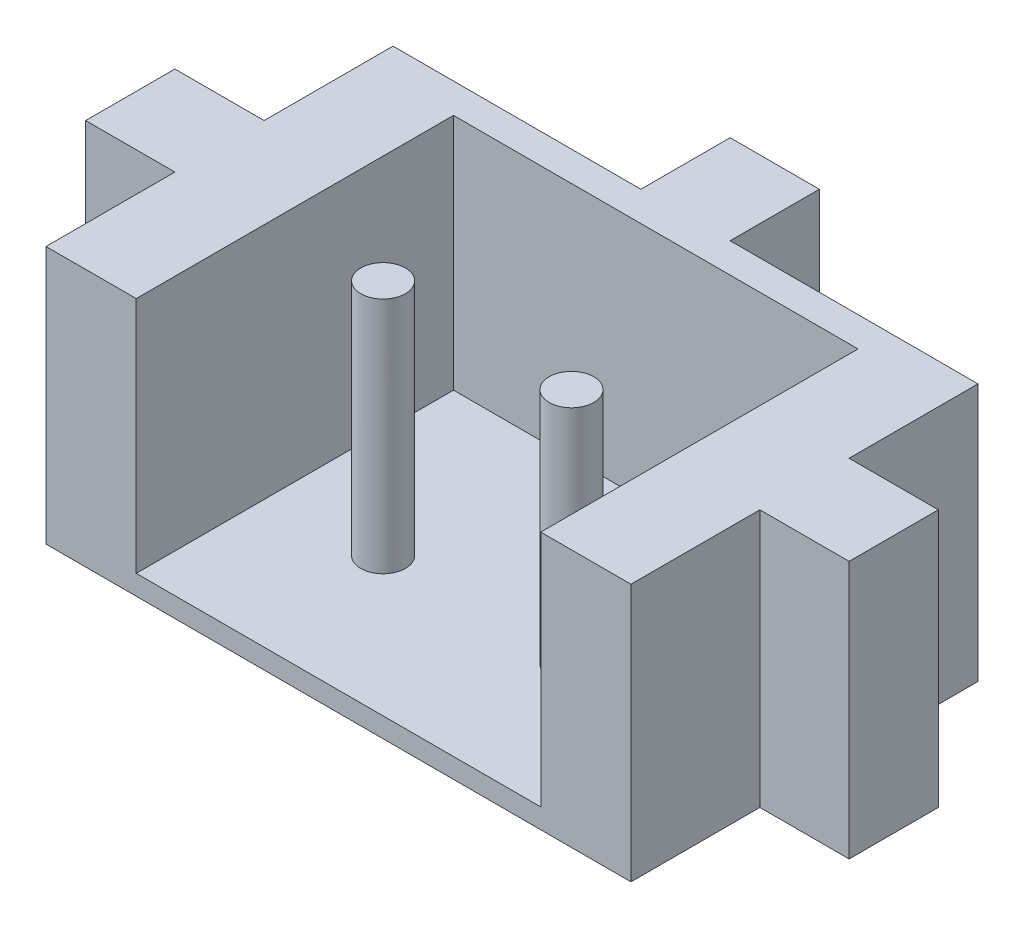
SolidWorks part; units mm, degrees
ref_plane "Alzado" through (0, 0, 0) normal (0, 0, 1) x (1, 0, 0)
ref_plane "Planta" through (0, 0, 0) normal (0, 1, 0) x (1, 0, 0)
ref_plane "Vista lateral" through (0, 0, 0) normal (1, 0, 0) x (0, 0, -1)
sketch "Croquis2" plane through (0, 0, 0) normal (0, 1, 0) x (1, 0, 0)
  line L0 (0, 10.287) -> (0, -10.6078) construction
  line L1 (14.75, -8.75) -> (-14.75, -8.75)
  line L2 (14.75, -8.75) -> (14.75, -2.25)
  line L3 (14.75, 8.75) -> (2.25, 8.75)
  line L4 (-14.75, -8.75) -> (-14.75, -2.25)
  line L5 (14.75, -8.75) -> (-14.75, 8.75) construction
  line L6 (14.75, 8.75) -> (-14.75, -8.75) construction
  line L7 (-10.7327, 0) -> (10.7937, 0) construction
  line L8 (19.25, -2.25) -> (14.75, -2.25)
  line L9 (2.25, 13.25) -> (-2.25, 13.25)
  line L10 (2.25, 13.25) -> (2.25, 8.75)
  line L12 (-2.25, 13.25) -> (-2.25, 8.75)
  line L13 (2.25, 13.25) -> (-2.25, 8.75) construction
  line L14 (2.25, 8.75) -> (-2.25, 13.25) construction
  line L15 (-19.25, 2.25) -> (-14.75, 2.25)
  line L16 (-19.25, 2.25) -> (-19.25, -2.25)
  line L17 (-19.25, -2.25) -> (-14.75, -2.25)
  line L19 (-19.25, 2.25) -> (-14.75, -2.25) construction
  line L20 (-19.25, -2.25) -> (-14.75, 2.25) construction
  line L22 (19.25, 2.25) -> (14.75, 2.25)
  line L23 (19.25, 2.25) -> (19.25, -2.25)
  line L32 (-2.25, 8.75) -> (-14.75, 8.75)
  line L33 (14.75, 2.25) -> (14.75, 8.75)
  line L34 (-14.75, 2.25) -> (-14.75, 8.75)
  point P0 (0, 0)
  point P10 (0, 11)
  point P15 (-17, 0)
  dimension "D1" = 4.5
  dimension "D2" = 4.5
  dimension "D3" = 4.5
  dimension "D4" = 4.5
  dimension "D5" = 29.5
  dimension "D6" = 17.5
extrude "Saliente-Extruir1" add sketch "Croquis2" along normal blind 13
sketch "Croquis4" plane through (0, 13, 0) normal (0, 1, 0) x (1, 0, 0)
  line L0 (-14.75, 8.75) -> (-14.75, -8.75) construction
  line L1 (-10.2, 7.25) -> (-10.2, -8.75)
  line L2 (-14.75, 8.75) -> (14.75, 8.75) construction
  line L3 (14.75, 8.75) -> (14.75, -8.75) construction
  line L6 (-10.2, 7.25) -> (10.2, 7.25)
  line L9 (0, 5.1469) -> (0, -6.906) construction
  line L10 (10.2, 7.25) -> (10.2, -8.75)
  line L11 (-10.2, -8.75) -> (10.2, -8.75)
  line L12 (-14.75, -8.75) -> (14.75, -8.75) construction
  circle A0 centre (4.75, -1.75) radius 1.125
  circle A1 centre (-4.75, -1.75) radius 1.125
  dimension "D4" = 2.25
  dimension "D6" = 4.75
  dimension "D2" = 7
  dimension "D1" = 10.2
  dimension "D3" = 1.5
extrude "Cortar-Extruir1" cut sketch "Croquis4" against normal offset from surface (12 mm away) 1 up to face at (0, 0, -2.75)
